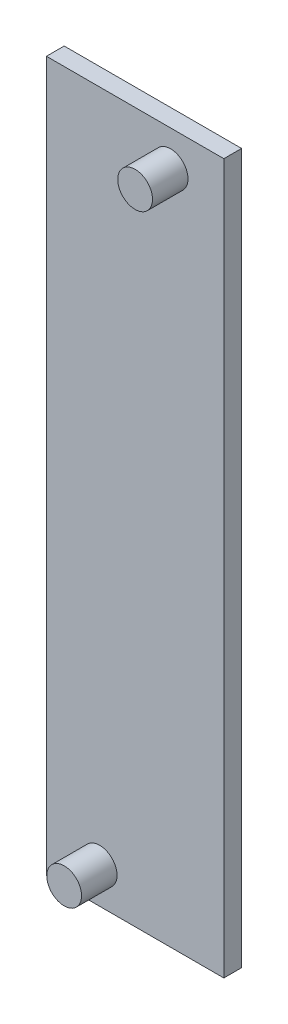
SolidWorks part; units mm, degrees
ref_plane "Front Plane" through (0, 0, 0) normal (0, 0, 1) x (1, 0, 0)
ref_plane "Top Plane" through (0, 0, 0) normal (0, 1, 0) x (1, 0, 0)
ref_plane "Right Plane" through (0, 0, 0) normal (1, 0, 0) x (0, 0, -1)
sketch "Sketch1" plane through (0, 0, 0) normal (0, 0, 1) x (1, 0, 0)
  line L1 (0, 0) -> (50, 0)
  line L2 (0, 0) -> (0, 200)
  line L3 (0, 200) -> (50, 200)
  line L4 (50, 0) -> (50, 200)
  dimension "D1" = 50
  dimension "D2" = 200
extrude "Boss-Extrude1" add sketch "Sketch1" along normal blind 5
sketch "Sketch2" plane through (0, 0, 5) normal (0, 0, 1) x (1, 0, 0)
  line L0 (0, 0) -> (50, 0) construction
  line L1 (0, 200) -> (0, 0) construction
  line L2 (50, 200) -> (0, 200) construction
  circle A0 centre (15, 10) radius 4.9
  circle A1 centre (35, 190) radius 4.9
  dimension "D1" = 9.8
  dimension "D2" = 10
  dimension "D3" = 15
  dimension "D4" = 10
  dimension "D5" = 9.8
  dimension "D6" = 20
extrude "Boss-Extrude2" add sketch "Sketch2" along normal blind 10
